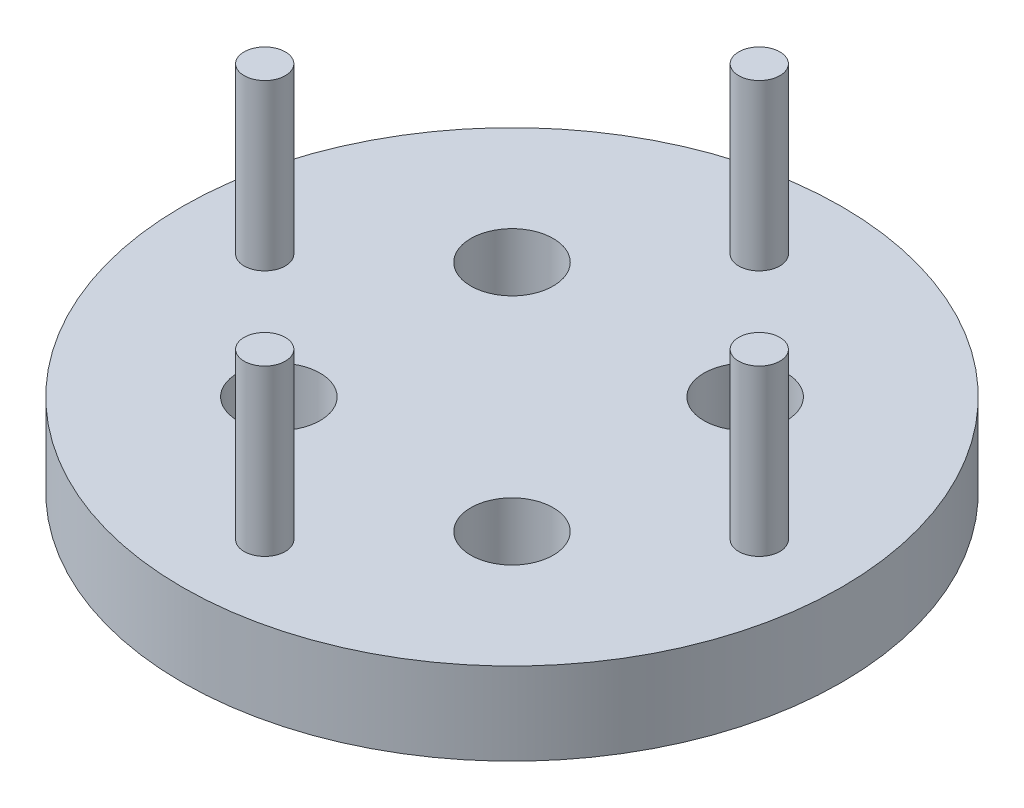
SolidWorks part; units mm, degrees
ref_plane "Front Plane" through (0, 0, 0) normal (0, 0, 1) x (1, 0, 0)
ref_plane "Top Plane" through (0, 0, 0) normal (0, 1, 0) x (1, 0, 0)
ref_plane "Right Plane" through (0, 0, 0) normal (1, 0, 0) x (0, 0, -1)
sketch "Sketch1" plane through (0, 0, 0) normal (0, 1, 0) x (1, 0, 0)
  circle A0 centre (0, 0) radius 25.4
  dimension "D1" = 50.8
extrude "Boss-Extrude1" add sketch "Sketch1" along normal blind 6.35 contours A0
sketch "Sketch2" plane through (0, 6.35, 0) normal (0, 1, 0) x (1, 0, 0)
  line L0 (0, 0) -> (-19.05, 0) construction
  circle A0 centre (-19.05, 0) radius 1.5875
  dimension "D1" = 3.175
  dimension "D2" = 19.05
extrude "Boss-Extrude2" add sketch "Sketch2" along normal blind 12.7
pattern_circular "CirPattern1" count 4 over 360 about axis through (0, 0, 0) along (0, 1, 0) of "Boss-Extrude2"
sketch "Sketch3" plane through (0, 0, 0) normal (0, -1, 0) x (1, 0, 0)
  line L0 (-8.9803, 8.9803) -> (8.9803, -8.9803) construction
  line L1 (0, 0) -> (-11.741, 0) construction
  circle A1 centre (8.9803, -8.9803) radius 3.175
  point P4 (0, 0)
  point P7 (12.2887, -12.7)
  dimension "D2" = 6.35
  dimension "D1" = 25.4
  dimension "D3" = 45
extrude "Cut-Extrude1" cut sketch "Sketch3" against normal through all
pattern_circular "CirPattern2" count 4 over 360 about axis through (0, 0, 0) along (0, 1, 0) of "Cut-Extrude1"
equation "\"R\"= 1.5in'radius of rotor"
equation "\"E\"= .125in'eccentricity"
equation "\"R_r\"= .125in'radius of roller"
equation "\"N\"= 9'number of rollers"
equation "\"R_o\"= .125in'output disk pin diameter"
equation "\"D1@Sketch2\"=\"R_r\""
equation "\"D2@Sketch2\"=\"R_off\""
equation "\"R_off\"= .75"
equation "\"D1@Sketch1\"=(\"R_off\"+\"R_o\"+.125)*2"
